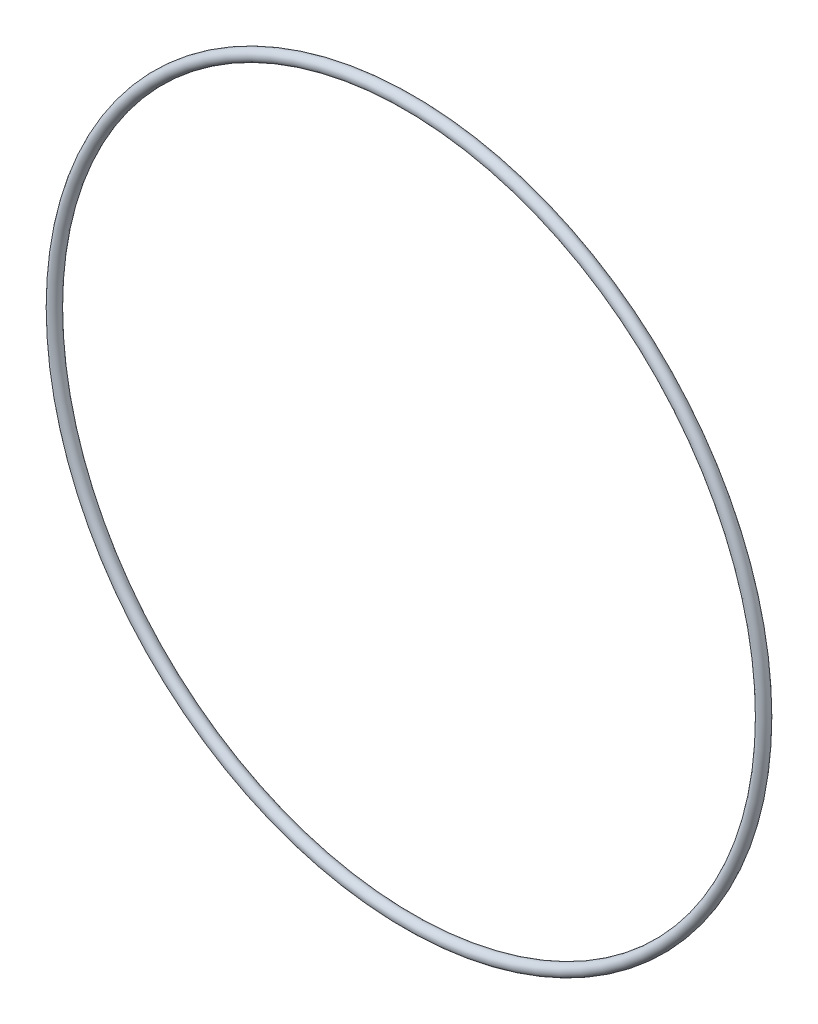
SolidWorks part; units mm, degrees
ref_plane "Front Plane" through (0, 0, 0) normal (0, 0, 1) x (1, 0, 0)
ref_plane "Top Plane" through (0, 0, 0) normal (0, 1, 0) x (1, 0, 0)
ref_plane "Right Plane" through (0, 0, 0) normal (1, 0, 0) x (0, 0, -1)
sketch "Sketch1" plane through (0, 0, 0) normal (0, 0, 1) x (1, 0, 0)
  line L0 (-46.5, 0) -> (46.5, 0) construction
  circle A0 centre (0, 0) radius 46.5
  circle A1 centre (0, 0) radius 45
  point P4 (45, 0)
  point P5 (46.5, 0)
  point P8 (0, 0)
  dimension "ID" = 90
  dimension "Width" = 1.5
  dimension "OD" = 93
sketch "Sketch2" plane through (0, 0, 0) normal (0, 1, 0) x (1, 0, 0)
  line L0 (-46.5, 0) -> (46.5, 0) construction
  line L1 (0, 0.75) -> (0, -0.75) construction
  circle A0 centre (45.75, 0) radius 0.75
  point P8 (0, 0)
  point P11 (45.75, 0.75)
revolve "Revolve1" add sketch "Sketch2" angle 360 about L1
sketch "Sketch3" plane through (0, 0, 0) normal (1, 0, 0) x (0, 0, -1)
  line L0 (-0.75, 0) -> (0.75, 0) construction
  line L1 (0.75, -45.75) -> (0.75, 45.75) construction
  point P2 (0, 0)
